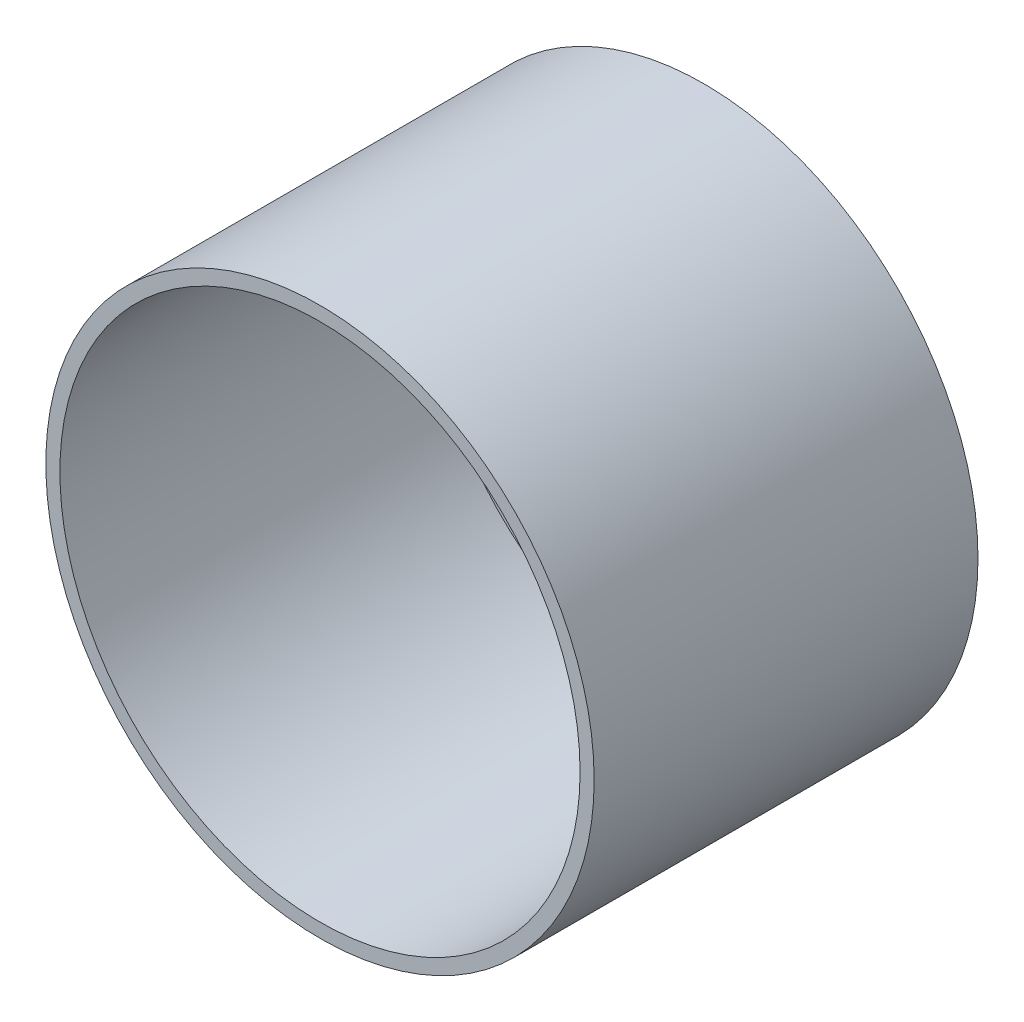
SolidWorks part; units mm, degrees
ref_plane "Plan de face" through (0, 0, 0) normal (0, 0, 1) x (1, 0, 0)
ref_plane "Plan de dessus" through (0, 0, 0) normal (0, 1, 0) x (1, 0, 0)
ref_plane "Plan de droite" through (0, 0, 0) normal (1, 0, 0) x (0, 0, -1)
sketch "Esquisse4" plane through (0, 0, 0) normal (0, 0, 1) x (1, 0, 0)
  circle A0 centre (0, 0) radius 75
  dimension "D1" = 150
extrude "Boss.-Extru.3" add sketch "Esquisse4" along normal blind 5
sketch "Esquisse5" plane through (0, 0, 5) normal (0, 0, 1) x (1, 0, 0)
  circle A0 centre (0, 0) radius 75
  circle A1 centre (0, 0) radius 71.1508
extrude "Boss.-Extru.4" add sketch "Esquisse5" along normal blind 100
